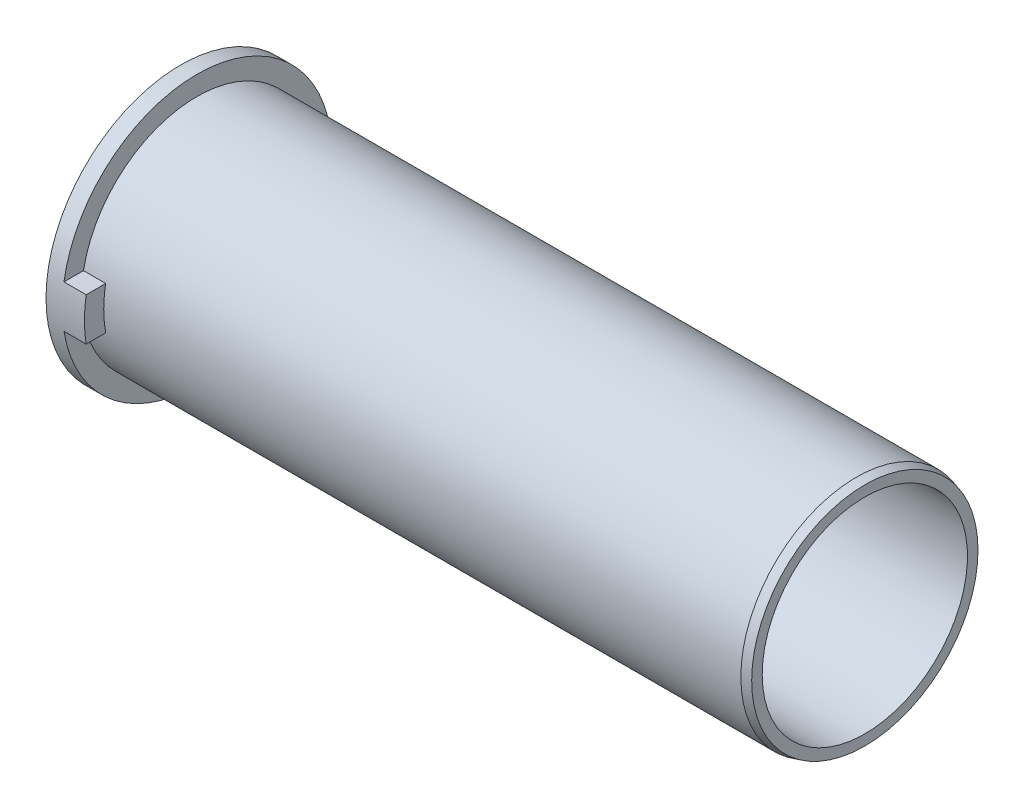
SolidWorks part; units mm, degrees
ref_plane "Plano frontal" through (0, 0, 0) normal (0, 0, 1) x (1, 0, 0)
ref_plane "Plano superior" through (0, 0, 0) normal (0, 1, 0) x (1, 0, 0)
ref_plane "Plano direito" through (0, 0, 0) normal (1, 0, 0) x (0, 0, -1)
sketch "Esboço1" plane through (0, 0, 0) normal (0, 0, 1) x (1, 0, 0)
  line L0 (0, 0) -> (17.1401, 0) construction
  line L1 (0.38, 2.7) -> (15.8, 2.7)
  line L2 (0, 3.15) -> (0.38, 3.15)
  line L3 (0.38, 3.15) -> (0.38, 2.7)
  line L4 (0, 3.15) -> (0, 2.3)
  line L5 (16, 2.6464) -> (16, 2.4)
  line L6 (15.8, 2.7) -> (16, 2.6464)
  line L7 (0, 2.3) -> (3.67, 2.3)
  line L8 (3.67, 2.3) -> (3.67, 1.8)
  line L9 (3.67, 1.8) -> (4.1004, 1.8)
  line L10 (4.1004, 1.8) -> (4.1004, 2.3)
  line L11 (4.1004, 2.3) -> (16, 2.4)
  dimension "D1" = 6.3
  dimension "D2" = 0.38
  dimension "D3" = 5.4
  dimension "D4" = 16
  dimension "D5" = 0.2
  dimension "D6" = 15
  dimension "D7" = 4.6
  dimension "D8" = 3.67
  dimension "D9" = 11.9
  dimension "D10" = 4.6
  dimension "D11" = 4.8
  dimension "D12" = 3.6
revolve "Revolução1" add sketch "Esboço1" angle 360 about L0
sketch "Esboço3" plane through (0.38, 0, 0) normal (1, 0, 0) x (0, 0, -1)
  line L4 (-3.1101, 0.5) -> (-2.6533, 0.5)
  line L5 (-3.1101, -0.5) -> (-2.6533, -0.5)
  line L6 (2.6533, -0.5) -> (3.1101, -0.5)
  line L7 (2.6533, 0.5) -> (3.1101, 0.5)
  arc A2 (3.1101, -0.5) -> (3.1101, 0.5) centre (0, 0) ccw
  arc A3 (-2.6533, 0.5) -> (-2.6533, -0.5) centre (0, 0) ccw
  arc A4 (2.6533, -0.5) -> (2.6533, 0.5) centre (0, 0) ccw
  arc A5 (-3.1101, 0.5) -> (-3.1101, -0.5) centre (0, 0) ccw
extrude "Ressalto-extrusão1" add sketch "Esboço3" along normal blind 0.52
